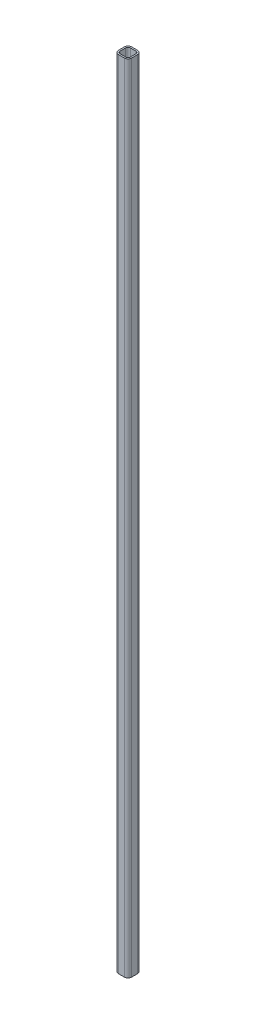
SolidWorks part; units mm, degrees
material "ABS"
ref_plane "Front" through (0, 0, 0) normal (0, 0, 1) x (1, 0, 0)
ref_plane "Top" through (0, 0, 0) normal (0, 1, 0) x (1, 0, 0)
ref_plane "Right" through (0, 0, 0) normal (1, 0, 0) x (0, 0, -1)
sketch "Эскиз1" plane through (0, 0, 0) normal (0, 1, 0) x (1, 0, 0)
  line L1 (-11, 11) -> (11, 11)
  line L2 (-11, 11) -> (-11, -11)
  line L3 (-11, -11) -> (11, -11)
  line L4 (11, 11) -> (11, -11)
  line L5 (-11, 11) -> (11, -11) construction
  line L6 (-11, -11) -> (11, 11) construction
  point P0 (0, 0)
  dimension "D1" = 22
  dimension "D2" = 22
extrude "Бобышка-Вытянуть1" add sketch "Эскиз1" along normal blind 1100 and the other way blind 90
sketch "Эскиз2" plane through (0, -90, 0) normal (0, -1, 0) x (1, 0, 0)
  line L1 (-11, 11) -> (11, 11)
  line L2 (-11, 11) -> (-11, -11)
  line L3 (-11, -11) -> (11, -11)
  line L4 (11, 11) -> (11, -11)
extrude "Бобышка-Вытянуть2" add sketch "Эскиз2" along normal blind 130
sketch "Sketch1" plane through (0, -220, 0) normal (0, -1, 0) x (1, 0, 0)
  line L0 (-11, 11) -> (-11, -11) construction
  line L1 (-8.5, 8.5) -> (8.5, 8.5)
  line L2 (-8.5, 8.5) -> (-8.5, -8.5)
  line L3 (-8.5, -8.5) -> (8.5, -8.5)
  line L4 (8.5, 8.5) -> (8.5, -8.5)
  line L5 (-8.5, 8.5) -> (8.5, -8.5) construction
  line L6 (-8.5, -8.5) -> (8.5, 8.5) construction
  line L7 (11, 11) -> (-11, 11) construction
  point P0 (0, 0)
  dimension "D1" = 2.5
  dimension "D2" = 2.5
extrude "Cut-Extrude1" cut sketch "Sketch1" against normal through all
fillet "Fillet2" radius 6 4 edges at (-11, 440, 11) (11, 440, 11) (-11, 440, -11) (11, 440, -11)
fillet "Fillet3" radius 4 4 edges at (8.5, 440, -8.5) (8.5, 440, 8.5) (-8.5, 440, 8.5) (-8.5, 440, -8.5)
